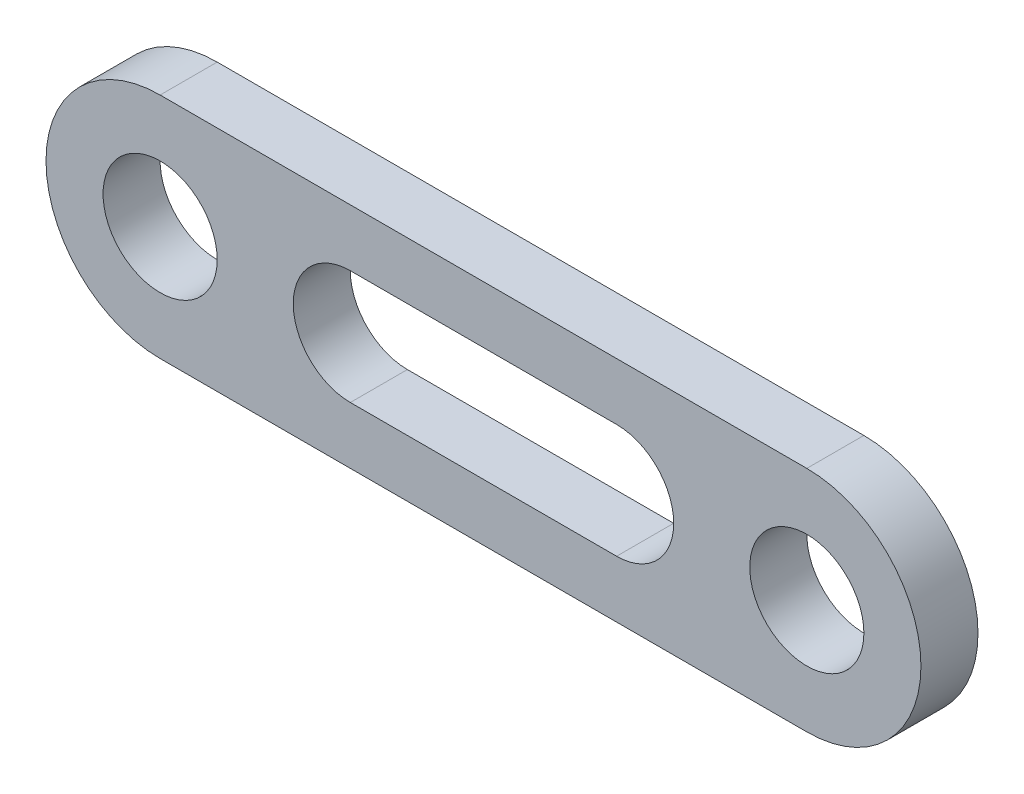
SolidWorks part; units mm, degrees
ref_plane "前视" through (0, 0, 0) normal (0, 0, 1) x (1, 0, 0)
ref_plane "上视" through (0, 0, 0) normal (0, 1, 0) x (1, 0, 0)
ref_plane "右视" through (0, 0, 0) normal (1, 0, 0) x (0, 0, -1)
sketch "草图2" plane through (0, 0, 0) normal (0, 0, 1) x (1, 0, 0)
  line L0 (0, 6) -> (34, 6)
  line L1 (0, -6) -> (34, -6)
  line L2 (10, 3) -> (24, 3)
  line L3 (10, -3) -> (24, -3)
  line L4 (-8.0174, 0) -> (37.0477, 0) construction
  arc A0 (0, 6) -> (0, -6) centre (0, 0) ccw
  arc A1 (34, -6) -> (34, 6) centre (34, 0) ccw
  circle A2 centre (0, 0) radius 3
  circle A3 centre (34, 0) radius 3
  arc A4 (10, 3) -> (10, -3) centre (10, 0) ccw
  arc A5 (24, -3) -> (24, 3) centre (24, 0) ccw
  dimension "D1" = 12
  dimension "D2" = 12
  dimension "D3" = 6
  dimension "D4" = 6
  dimension "D8" = 6
  dimension "D9" = 6
  dimension "D5" = 34
  dimension "D6" = 10
  dimension "D7" = 10
extrude "凸台-拉伸1" add sketch "草图2" along normal blind 3
